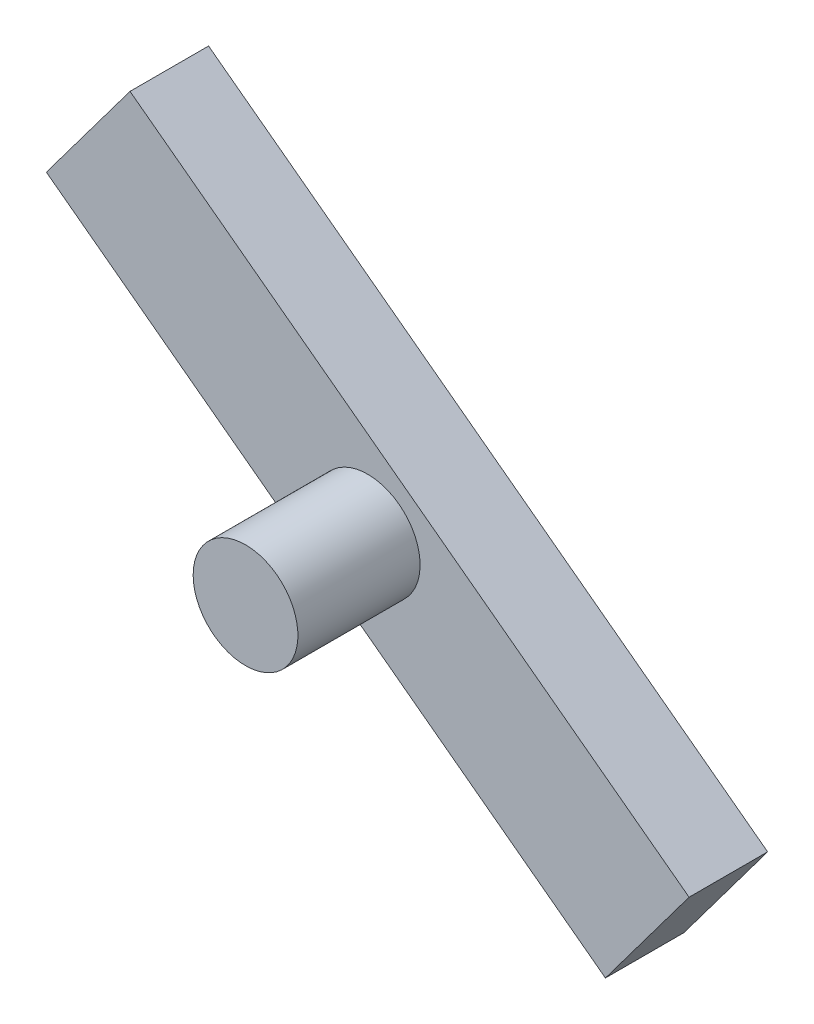
SolidWorks part; units mm, degrees
ref_plane "Alzado" through (0, 0, 0) normal (0, 0, 1) x (1, 0, 0)
ref_plane "Planta" through (0, 0, 0) normal (0, 1, 0) x (1, 0, 0)
ref_plane "Vista lateral" through (0, 0, 0) normal (1, 0, 0) x (0, 0, -1)
sketch3d "Sk_Vastago"
  line L0 (-263.1284, 316.5049, 22) -> (-263.1284, 316.5049, 15)
sweep "Vastago" add path "Sk_Vastago" circular profile diameter 6 parameters "D3"=6
sketch "Sk_Goma" plane through (0, 0, 0) normal (0, 0, 1) x (1, 0, 0)
  line L0 (-249.5118, 301.3198) -> (-244.7188, 307.725)
  line L1 (-244.7188, 307.725) -> (-276.7449, 331.6901)
  line L2 (-276.7449, 331.6901) -> (-281.538, 325.2848)
  line L3 (-281.538, 325.2848) -> (-249.5118, 301.3198)
extrude "Goma" add sketch "Sk_Goma" along normal blind 4.5 from offset 10.5
